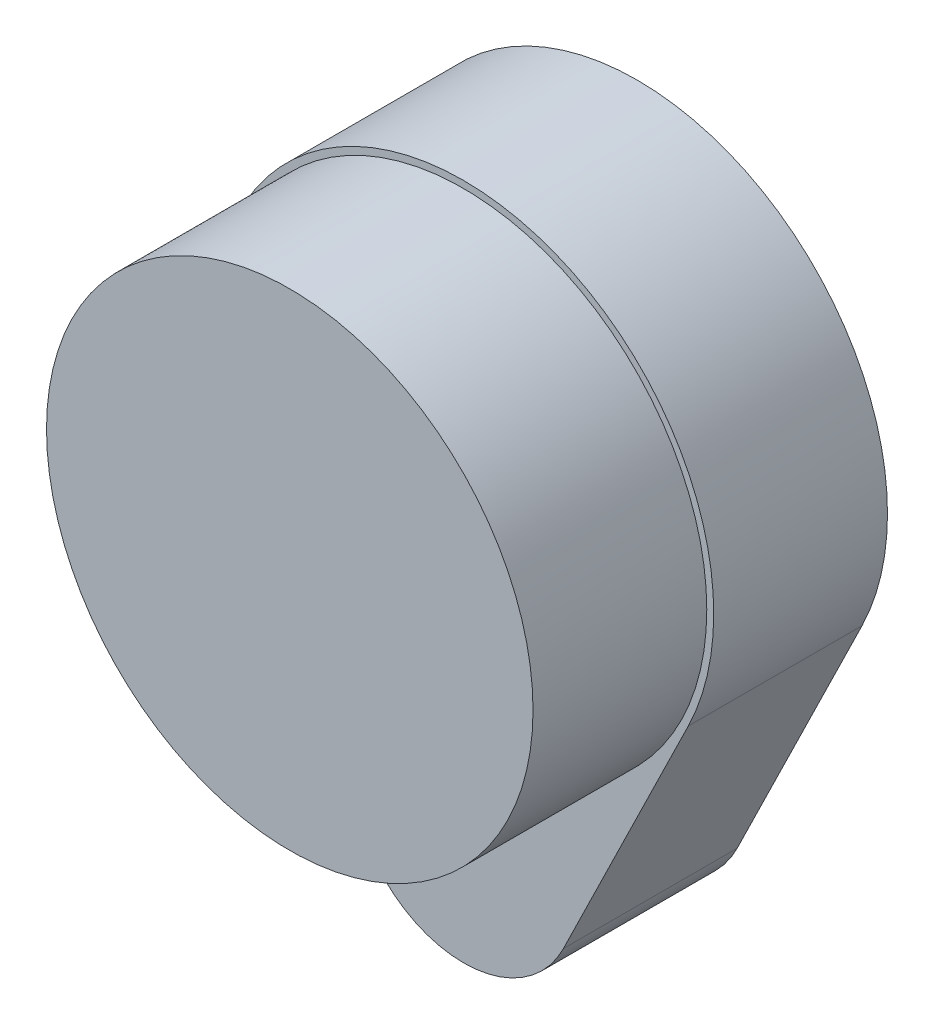
SolidWorks part; units mm, degrees
ref_plane "前视基准面" through (0, 0, 0) normal (0, 0, 1) x (1, 0, 0)
ref_plane "上视基准面" through (0, 0, 0) normal (0, 1, 0) x (1, 0, 0)
ref_plane "右视基准面" through (0, 0, 0) normal (1, 0, 0) x (0, 0, -1)
ref_plane "基准面4" through (0, 0, 20) normal (0, 0, 1) x (1, 0, 0)
sketch "草图1" plane through (0, 0, 20) normal (0, 0, 1) x (1, 0, 0)
  line L0 (14.3714, -44.033) -> (32.3357, -7.3242)
  line L1 (-32.3357, -7.3242) -> (-14.3714, -44.033)
  line L2 (0, 8.5) -> (0, -60.4754) construction
  arc A0 (32.3357, -7.3242) -> (-32.3357, -7.3242) centre (0, 8.5) ccw
  arc A1 (-14.3714, -44.033) -> (14.3714, -44.033) centre (0, -37) ccw
  dimension "D1" = 36
  dimension "D2" = 16
  dimension "D3" = 45.5
extrude "凸台-拉伸1" add sketch "草图1" against normal blind 25
ref_plane "基准面5" through (0, 0, 20) normal (0, 0, -1) x (-1, 0, 0)
sketch "草图2" plane through (0, 0, 20) normal (0, 0, -1) x (-1, 0, 0)
  circle A0 centre (0, 8.5) radius 35
  arc A1 (32.3357, -7.3242) -> (-32.3357, -7.3242) centre (0, 8.5) ccw construction
extrude "凸台-拉伸2" add sketch "草图2" against normal blind 25
hole_wizard "Ø3.0 (3) 直径孔1" positions "草图4" profile "草图3" hole size "Ø3.0" standard "ANSI Metric"
sketch "草图4" plane through (0, 0, -5) normal (0, 0, -1) x (-1, 0, 0)
  point P0 (0, 0)
  point P1 (0, -37)
sketch "草图3" plane through (0, 0, -5) normal (1, 0, 0) x (0, 1, 0)
  line L0 (0, 0) -> (0, 5)
  line L1 (0, 5) -> (1.5, 5)
  line L2 (1.5, 5) -> (1.5, 0)
  line L5 (1.5, 0) -> (0, 0)
  line L10 (0, 5) -> (-1.5, 5) construction
  line L11 (0, -6.35) -> (0, 107.95) construction
  dimension "孔直径" = 3
  dimension "孔深度" = 5
  dimension "导头角度" = 180
ref_plane "基准面6" through (0, 0, 0) normal (1, 0, 0) x (0, 0, -1)
